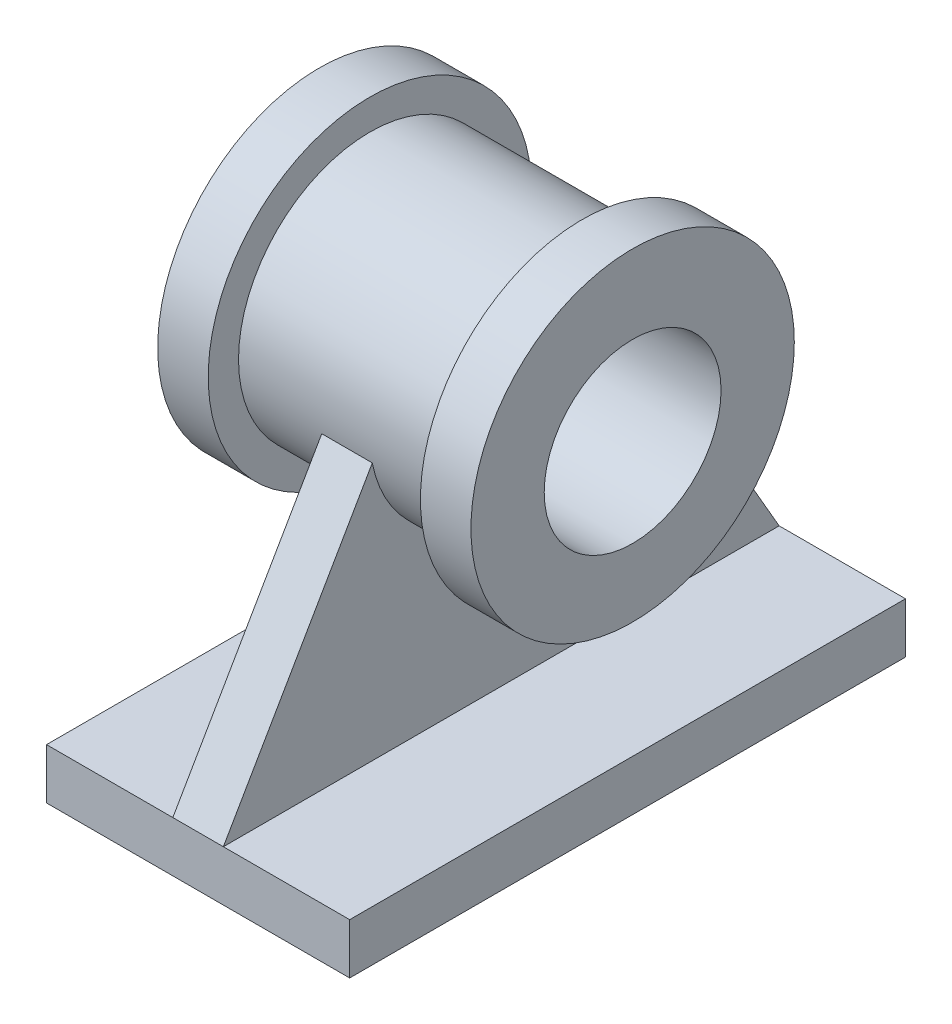
SolidWorks part; units mm, degrees
ref_plane "정면" through (0, 0, 0) normal (0, 0, 1) x (1, 0, 0)
ref_plane "윗면" through (0, 0, 0) normal (0, 1, 0) x (1, 0, 0)
ref_plane "우측면" through (0, 0, 0) normal (1, 0, 0) x (0, 0, -1)
sketch "스케치1" plane through (0, 0, 0) normal (0, 1, 0) x (1, 0, 0)
  line L1 (-30, 55) -> (30, 55)
  line L2 (-30, 55) -> (-30, -55)
  line L3 (-30, -55) -> (30, -55)
  line L4 (30, 55) -> (30, -55)
  line L5 (-30, 55) -> (30, -55) construction
  line L6 (-30, -55) -> (30, 55) construction
  point P0 (0, 0)
  dimension "D1" = 110
  dimension "D2" = 60
extrude "보스-돌출1" add sketch "스케치1" along normal blind 10
sketch "스케치2" plane through (0, 10, 0) normal (0, 1, 0) x (1, 0, 0)
  line L0 (-30, -55) -> (30, -55) construction
  line L1 (-5, 55) -> (5, 55)
  line L2 (-5, 55) -> (-5, -55)
  line L3 (-5, -55) -> (5, -55)
  line L4 (5, 55) -> (5, -55)
  line L5 (-5, 55) -> (5, -55) construction
  line L6 (-5, -55) -> (5, 55) construction
  point P0 (0, 0)
  dimension "D1" = 10
extrude "보스-돌출2" add sketch "스케치2" along normal blind 85
sketch "스케치3" plane through (5, 0, 0) normal (1, 0, 0) x (0, 0, -1)
  line L0 (-55, 10) -> (-1.9272, 101.9247)
  line L1 (-1.9272, 101.9247) -> (-74.6708, 101.9247)
  line L3 (-74.6708, 101.9247) -> (-74.6708, 10)
  line L4 (-74.6708, 10) -> (-55, 10)
  line L5 (-55, 95) -> (-55, 10) construction
  dimension "D1" = 30
extrude "컷-돌출1" cut sketch "스케치3" against normal blind 85
mirror "대칭 복사1" about plane through (0, 0, 0) normal (0, 0, 1) of "컷-돌출1"
sketch "스케치4" plane through (0, 0, 0) normal (1, 0, 0) x (0, 0, -1)
  line L1 (-55, 0) -> (55, 0) construction
  circle A0 centre (0, 66) radius 26
  dimension "D2" = 52
  dimension "D1" = 66
extrude "보스-돌출3" add sketch "스케치4" along normal mid plane 42
sketch "스케치5" plane through (21, 0, 0) normal (1, 0, 0) x (0, 0, -1)
  line L0 (-16.8545, 85.7971) -> (-12.4429, 105.7472)
  line L1 (-12.4429, 105.7472) -> (16.0495, 102.3209)
  line L2 (16.0495, 102.3209) -> (20.0273, 82.5803)
  arc A0 (-16.8545, 85.7971) -> (20.0273, 82.5803) centre (0, 66) cw
  circle A1 centre (0, 66) radius 26 construction
extrude "컷-돌출2" cut sketch "스케치5" against normal blind 42
sketch "스케치6" plane through (21, 0, 0) normal (1, 0, 0) x (0, 0, -1)
  circle A0 centre (0, 66) radius 32
  dimension "D1" = 64
extrude "보스-돌출4" add sketch "스케치6" along normal blind 10
mirror "대칭 복사2" about plane through (0, 0, 0) normal (1, 0, 0) of "보스-돌출4"
sketch "스케치7" plane through (31, 0, 0) normal (1, 0, 0) x (0, 0, -1)
  circle A0 centre (0, 64.9673) radius 17.5
  dimension "D1" = 35
extrude "컷-돌출3" cut sketch "스케치7" against normal blind 81
